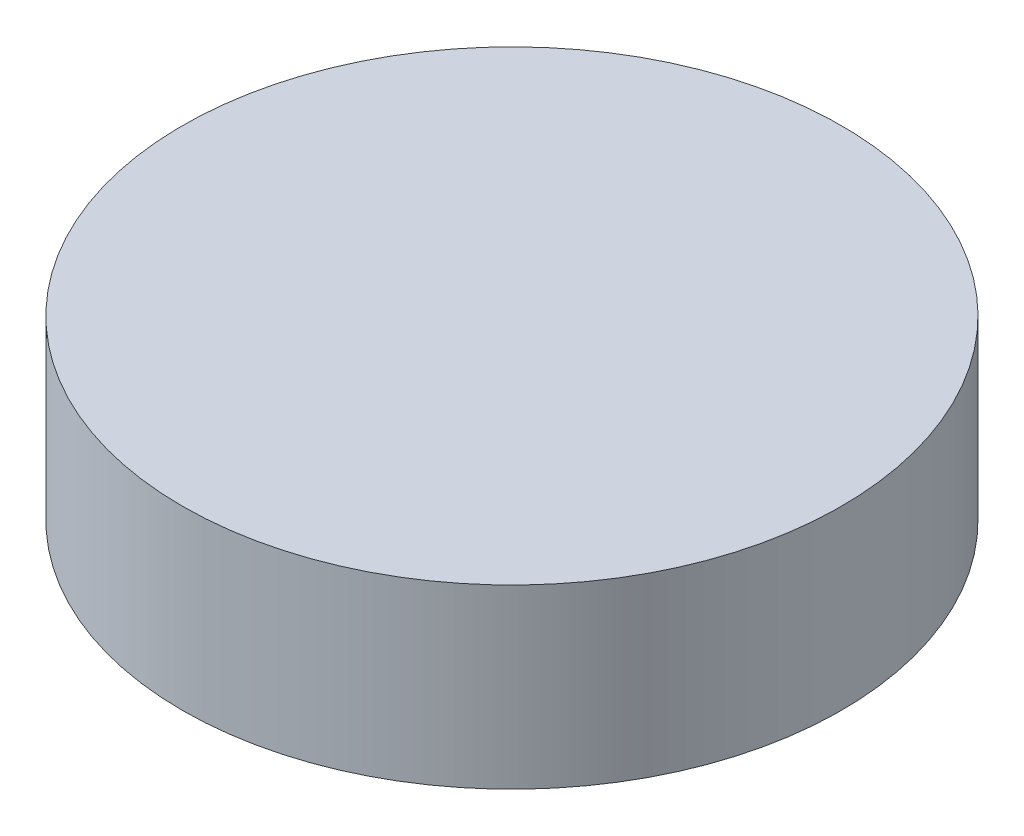
SolidWorks part; units mm, degrees
ref_plane "Front Plane" through (0, 0, 0) normal (0, 0, 1) x (1, 0, 0)
ref_plane "Top Plane" through (0, 0, 0) normal (0, 1, 0) x (1, 0, 0)
ref_plane "Right Plane" through (0, 0, 0) normal (1, 0, 0) x (0, 0, -1)
sketch "Sketch1" plane through (0, 0, 0) normal (0, 1, 0) x (1, 0, 0)
  circle A0 centre (0, 0) radius 14.2
  dimension "D1" = 28.4
extrude "Boss-Extrude1" add sketch "Sketch1" along normal blind 7.62
